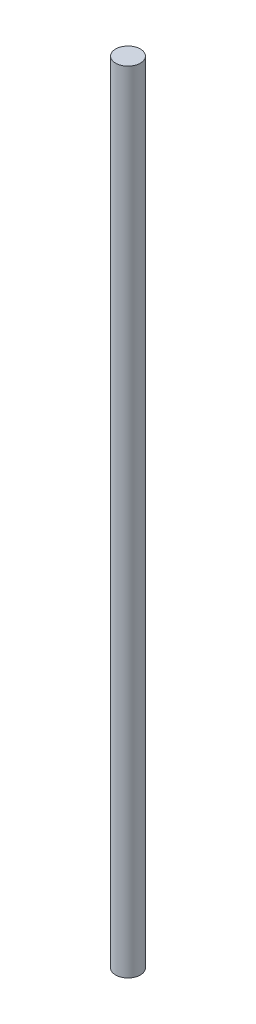
SolidWorks part; units mm, degrees
ref_plane "Front Plane" through (0, 0, 0) normal (0, 0, 1) x (1, 0, 0)
ref_plane "Top Plane" through (0, 0, 0) normal (0, 1, 0) x (1, 0, 0)
ref_plane "Right Plane" through (0, 0, 0) normal (1, 0, 0) x (0, 0, -1)
sketch "Sketch1" plane through (0, 0, 0) normal (0, 1, 0) x (1, 0, 0)
  circle A0 centre (0, 0) radius 0.5
extrude "Boss-Extrude1" add sketch "Sketch1" along normal blind 32
